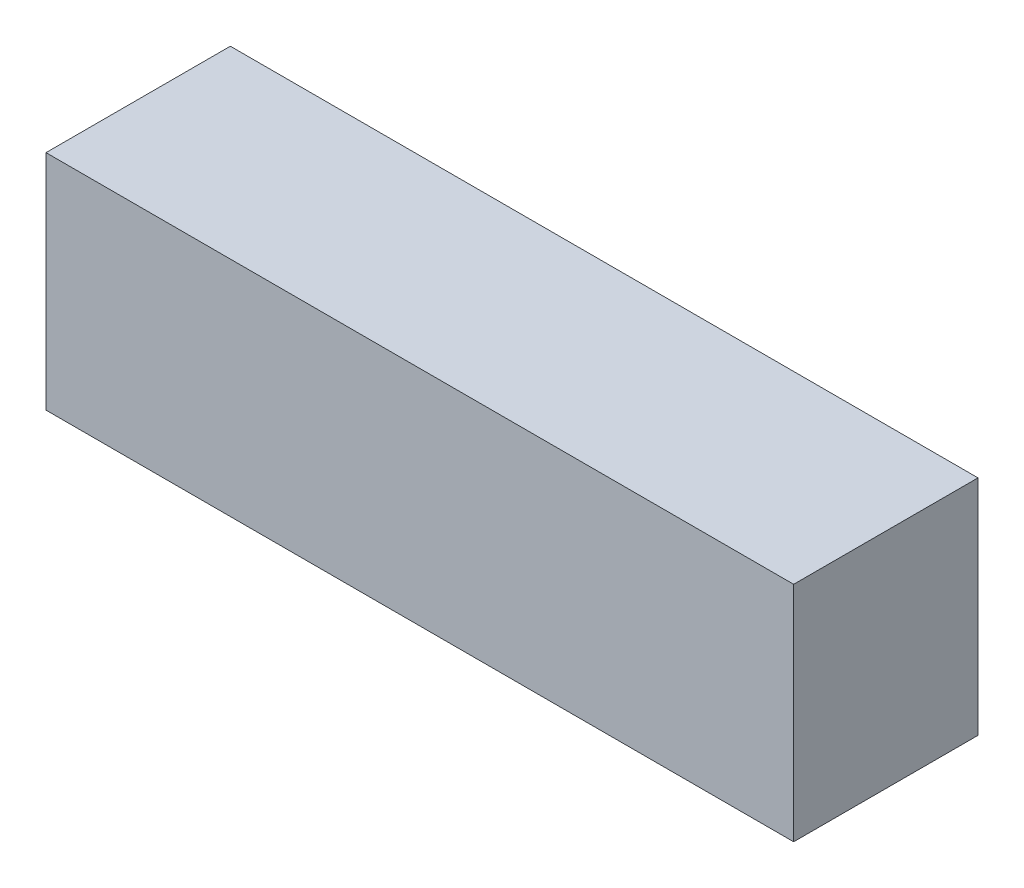
SolidWorks part; units mm, degrees
ref_plane "Front Plane" through (0, 0, 0) normal (0, 0, 1) x (1, 0, 0)
ref_plane "Top Plane" through (0, 0, 0) normal (0, 1, 0) x (1, 0, 0)
ref_plane "Right Plane" through (0, 0, 0) normal (1, 0, 0) x (0, 0, -1)
sketch "Sketch1" plane through (0, 0, 0) normal (0, 0, 1) x (1, 0, 0)
  line L1 (0, 0) -> (147.32, 0)
  line L2 (0, 0) -> (0, 43.942)
  line L3 (0, 43.942) -> (147.32, 43.942)
  line L4 (147.32, 0) -> (147.32, 43.942)
  dimension "D1" = 43.942
  dimension "D2" = 147.32
extrude "Boss-Extrude1" add sketch "Sketch1" along normal blind 36.322
